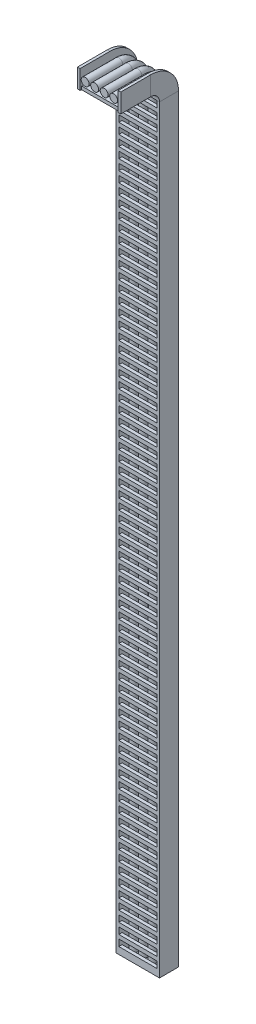
SolidWorks part; units mm, degrees
ref_plane "Alzado" through (0, 0, 0) normal (0, 0, 1) x (1, 0, 0)
ref_plane "Planta" through (0, 0, 0) normal (0, 1, 0) x (1, 0, 0)
ref_plane "Vista lateral" through (0, 0, 0) normal (1, 0, 0) x (0, 0, -1)
sketch "Croquis1" plane through (0, 0, 0) normal (0, 1, 0) x (1, 0, 0)
  line L1 (-165, 72.5) -> (165, 72.5)
  line L2 (-165, 72.5) -> (-165, -72.5)
  line L3 (-165, -72.5) -> (165, -72.5)
  line L4 (165, 72.5) -> (165, -72.5)
  line L5 (-165, 72.5) -> (165, -72.5) construction
  line L6 (-165, -72.5) -> (165, 72.5) construction
  point P0 (0, 0)
  dimension "D1" = 330
  dimension "D2" = 145
extrude "Saliente-Extruir1" add sketch "Croquis1" along normal blind 10
sketch "Croquis2" plane through (0, 10, 0) normal (0, 1, 0) x (1, 0, 0)
  line L0 (-165, -72.5) -> (165, -72.5)
  line L1 (165, -72.5) -> (165, 72.5)
  line L2 (165, 72.5) -> (145, 72.5)
  line L3 (165, 72.5) -> (-165, 72.5) construction
  line L4 (145, 72.5) -> (145, -47.5)
  line L5 (145, -47.5) -> (-145, -47.5)
  line L6 (-145, -47.5) -> (-145, 72.5)
  line L7 (-145, 72.5) -> (-165, 72.5)
  line L8 (-165, 72.5) -> (-165, -72.5)
  dimension "D1" = 20
  dimension "D2" = 20
  dimension "D3" = 25
sketch3d "Croquis3D1"
  line L0 (0, 0, 0) -> (0, 5782.5, 0)
  line L1 (0, 5922.5, 140) -> (0, 5922.5, 367.5)
  arc A0 (0, 5782.5, 0) -> (0, 5922.5, 140) centre (0, 5782.5, 140) ccw
  point P7 (0, 5922.5, 0)
  point P8 (140, 5782.5, 140)
  dimension "D2" = 140
  dimension "D1" = 5922.5
  dimension "D3" = 367.5
sweep "Barrer1" add profiles "Croquis2" path "Croquis3D1"
sketch "Croquis3" plane through (0, 0, 47.5) normal (0, 0, -1) x (-1, 0, 0)
  line L0 (-145, 52.7499) -> (145, 52.7499)
  line L1 (-145, 10) -> (-145, 5782.5) construction
  line L2 (145, 10) -> (145, 5782.5) construction
  line L3 (145, 52.7499) -> (145, 102.5739)
  line L4 (145, 102.5739) -> (-145, 102.5739)
  line L5 (-145, 10) -> (-145, 5782.5) construction
  line L6 (-145, 102.5739) -> (-145, 52.7499)
extrude "Cortar-Extruir1" cut sketch "Croquis3" against normal blind 66
pattern_linear "MatrizL1" count 73 spacing 80 along (0, 1, 0) of "Cortar-Extruir1"
sketch "Croquis4" plane through (0, 5875, 0) normal (0, 1, 0) x (1, 0, 0)
  line L0 (145, -116.8461) -> (-145, -116.8461)
  line L1 (145, -93.6921) -> (145, -140) construction
  line L2 (-145, -140) -> (-145, -93.6921) construction
  line L3 (-145, -116.8461) -> (-145, -150.8997)
  line L4 (-145, -150.8997) -> (145, -150.8997)
  line L5 (145, -140) -> (145, -367.5) construction
  line L6 (145, -150.8997) -> (145, -116.8461)
extrude "Cortar-Extruir2" cut sketch "Croquis4" against normal blind 66
pattern_linear "MatrizL2" count 4 spacing 80 along (0, 0, 1) of "Cortar-Extruir2"
sketch "Croquis5" plane through (0, 10, 0) normal (0, 1, 0) x (1, 0, 0)
  line L0 (145, 0) -> (-145, 0) construction
  line L1 (145, 72.5) -> (145, -47.5) construction
  line L2 (-145, -47.5) -> (-145, 72.5) construction
  line L3 (145, -47.5) -> (145, 72.5) construction
  line L4 (145, 72.5) -> (145, 12.5) construction
  line L5 (145, 12.5) -> (-145, 12.5) construction
  circle A0 centre (107.9566, 12.5) radius 30
  circle A1 centre (35.4566, 12.5) radius 30
  circle A2 centre (-109.5434, 12.5) radius 30
  circle A3 centre (-37.0434, 12.5) radius 30
  point P21 (-123.226, 12.5)
  point P22 (72.5, 12.5)
  point P23 (-53.3004, 12.5)
  point P24 (27.3879, 12.5)
  point P25 (110.3428, 12.5)
  point P26 (40.0805, 12.5)
  point P27 (-31.995, 12.5)
  point P28 (-103.1639, 12.5)
  point P29 (110.2505, 12.5)
  point P30 (0, 0)
  point P31 (107.9566, 12.5)
  dimension "D1" = 72.5
  dimension "D2" = 72.5
  dimension "D3" = 60
  dimension "D4" = 60
  dimension "D5" = 72.5
sketch3d "Croquis3D2"
  line L0 (107.9566, 10, -12.5) -> (107.9566, 5803.6282, -12.5)
  line L1 (107.9566, 5923.6282, 107.5) -> (107.9566, 5923.6282, 364.7842)
  arc A0 (107.9566, 5803.6282, -12.5) -> (107.9566, 5923.6282, 107.5) centre (107.9566, 5803.6282, 107.5) ccw
  point P6 (107.9566, 5923.6282, -12.5)
  point P7 (227.9566, 5803.6282, 107.5)
  dimension "D1" = 120
  dimension "D2" = 5913.6282
sweep "Barrer2" add profiles "Croquis5" path "Croquis3D2"
